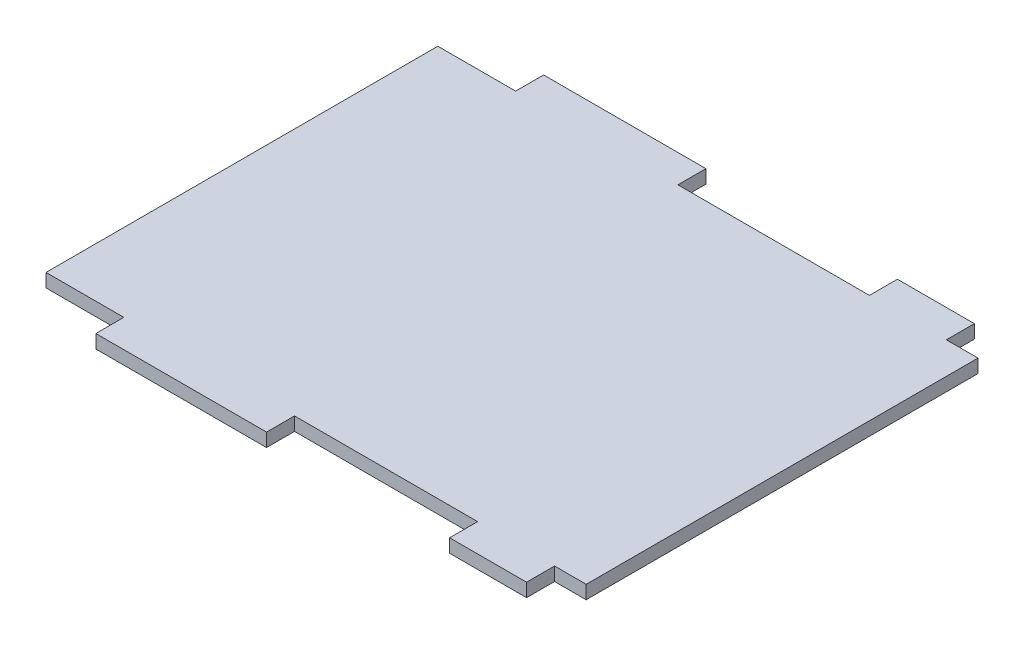
SolidWorks part; units mm, degrees
ref_plane "Front Plane" through (0, 0, 0) normal (0, 0, 1) x (1, 0, 0)
ref_plane "Top Plane" through (0, 0, 0) normal (0, 1, 0) x (1, 0, 0)
ref_plane "Right Plane" through (0, 0, 0) normal (1, 0, 0) x (0, 0, -1)
sketch "Sketch1" plane through (0, 0, 0) normal (0, 1, 0) x (1, 0, 0)
  line L1 (-96.5, -70) -> (96.5, -70)
  line L2 (-96.5, -70) -> (-96.5, 70)
  line L3 (-96.5, 70) -> (96.5, 70)
  line L4 (96.5, -70) -> (96.5, 70)
  line L5 (-96.5, -70) -> (96.5, 70) construction
  line L6 (-96.5, 70) -> (96.5, -70) construction
  line L7 (-68.7, -70) -> (-7.7, -70)
  line L8 (-68.7, -70) -> (-68.7, -80)
  line L9 (-68.7, -80) -> (-7.7, -80)
  line L10 (-7.7, -70) -> (-7.7, -80)
  line L11 (-68.7, 70) -> (-10.7183, 70)
  line L12 (-68.7, 70) -> (-68.7, 80)
  line L13 (-68.7, 80) -> (-10.7183, 80)
  line L14 (-10.7183, 70) -> (-10.7183, 80)
  line L15 (57.7138, 70) -> (85.1966, 70)
  line L16 (57.7138, 70) -> (57.7138, 80)
  line L17 (57.7138, 80) -> (85.1966, 80)
  line L18 (85.1966, 70) -> (85.1966, 80)
  line L19 (57.7138, -70) -> (85.1966, -70)
  line L20 (57.7138, -70) -> (57.7138, -80)
  line L21 (57.7138, -80) -> (85.1966, -80)
  line L22 (85.1966, -70) -> (85.1966, -80)
  point P0 (0, 0)
  point P6 (-68.7, -70)
  dimension "D1" = 193
  dimension "D2" = 140
  dimension "D3" = 27.8
  dimension "D4" = 10
  dimension "D5" = 10
  dimension "D6" = 10
  dimension "D7" = 10
  dimension "D8" = 68.4321
  dimension "D9" = 65.4138
  dimension "D10" = 27.4828
extrude "Boss-Extrude1" add sketch "Sketch1" along normal blind 4.8 contours L1 L4 L3 L2 | L3 L14 L13 L12 | L3 L18 L17 L16 | L22 L1 L20 L21 | L10 L1 L8 L9
